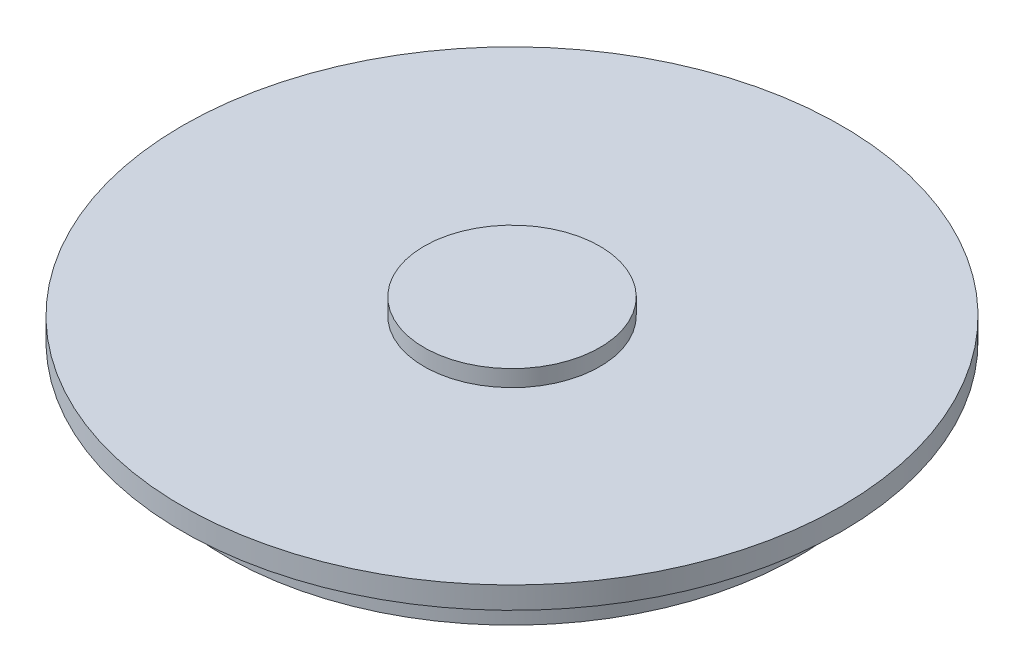
SolidWorks part; units mm, degrees
ref_plane "Front Plane" through (0, 0, 0) normal (0, 0, 1) x (1, 0, 0)
ref_plane "Top Plane" through (0, 0, 0) normal (0, 1, 0) x (1, 0, 0)
ref_plane "Right Plane" through (0, 0, 0) normal (1, 0, 0) x (0, 0, -1)
sketch "Sketch1" plane through (0, 0, 0) normal (0, 0, 1) x (1, 0, 0)
  line L0 (0, 0) -> (48, 0)
  line L1 (48, 0) -> (48, -8)
  line L2 (48, -8) -> (52, -8)
  line L3 (52, -8) -> (52, 0)
  line L4 (52, 0) -> (60, 0)
  line L5 (60, 0) -> (60, 4)
  line L6 (60, 4) -> (16, 4)
  line L7 (16, 4) -> (16, 7)
  line L8 (16, 7) -> (0, 7)
  line L9 (0, 7) -> (0, 0)
  dimension "D1" = 48
  dimension "D2" = 8
  dimension "D3" = 4
  dimension "D4" = 8
  dimension "D5" = 4
  dimension "D6" = 3
  dimension "D7" = 16
revolve "Lid Revolve" add sketch "Sketch1" angle 360 about L9
